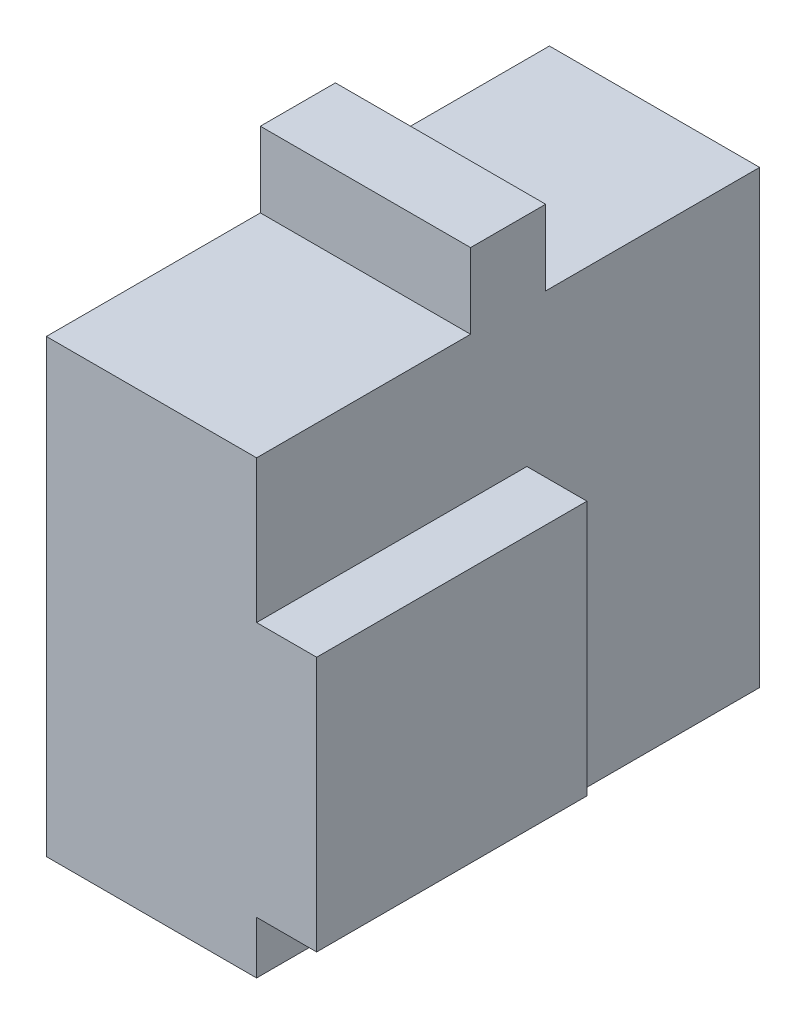
SolidWorks part; units mm, degrees
ref_plane "Front Plane" through (0, 0, 0) normal (0, 0, 1) x (1, 0, 0)
ref_plane "Top Plane" through (0, 0, 0) normal (0, 1, 0) x (1, 0, 0)
ref_plane "Right Plane" through (0, 0, 0) normal (1, 0, 0) x (0, 0, -1)
sketch "Sketch1" plane through (0, 0, 0) normal (1, 0, 0) x (0, 0, -1)
  line L1 (-33.5, 30) -> (33.5, 30)
  line L2 (-33.5, 30) -> (-33.5, -30)
  line L3 (-33.5, -30) -> (33.5, -30)
  line L4 (33.5, 30) -> (33.5, -30)
  point P4 (0, 30)
  point P6 (33.5, 0)
  dimension "D1" = 67
  dimension "D2" = 60
extrude "Boss-Extrude1" add sketch "Sketch1" along normal blind 28
sketch "Sketch3" plane through (28, 0, 0) normal (1, 0, 0) x (0, 0, -1)
  line L0 (-33.5, 30) -> (-33.5, -30) construction
  line L1 (-33.5, -23) -> (2.5, -23)
  line L2 (-33.5, -23) -> (-33.5, 11)
  line L3 (-33.5, 11) -> (2.5, 11)
  line L4 (2.5, -23) -> (2.5, 11)
  line L5 (-33.5, -30) -> (33.5, -30) construction
  dimension "D1" = 7
  dimension "D2" = 36
  dimension "D3" = 34
extrude "Boss-Extrude2" add sketch "Sketch3" along normal blind 8
sketch "Sketch4" plane through (0, 30, 0) normal (0, 1, 0) x (1, 0, 0)
  line L0 (28, 33.5) -> (28, -33.5) construction
  line L1 (28, -5) -> (0, -5)
  line L2 (28, -5) -> (28, 5)
  line L3 (28, 5) -> (0, 5)
  line L4 (0, -5) -> (0, 5)
  point P4 (0, 0)
  point P6 (28, 0)
  point P9 (28, 0)
  dimension "D1" = 10
extrude "Boss-Extrude3" add sketch "Sketch4" along normal blind 10
